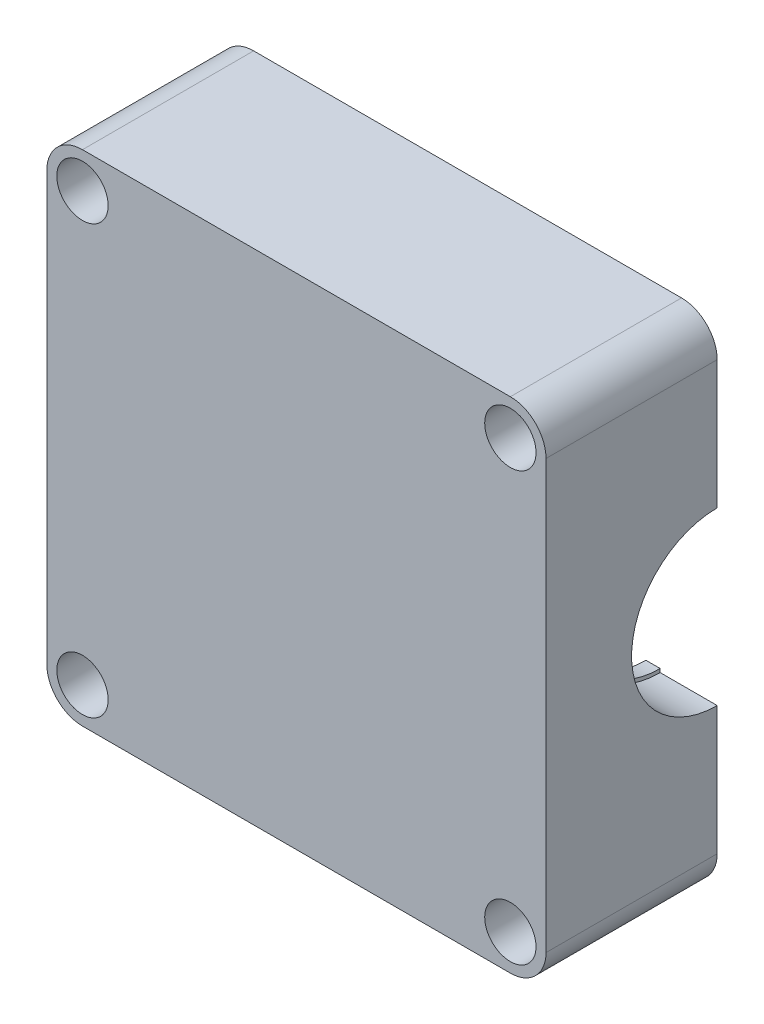
SolidWorks part; units mm, degrees
ref_plane "前视基准面" through (0, 0, 0) normal (0, 0, 1) x (1, 0, 0)
ref_plane "上视基准面" through (0, 0, 0) normal (0, 1, 0) x (1, 0, 0)
ref_plane "右视基准面" through (0, 0, 0) normal (1, 0, 0) x (0, 0, -1)
other "Configuration Table"
sketch "草图1" plane through (0, 0, 0) normal (0, 0, 1) x (-1, 0, 0)
  line L8 (-17.5, 15) -> (-17.5, -15)
  line L9 (-15, -17.5) -> (15, -17.5)
  line L10 (17.5, -15) -> (17.5, 15)
  line L11 (15, 17.5) -> (-15, 17.5)
  line L16 (15.6047, -11.417) -> (15.6047, 11.417)
  line L17 (-11.417, -15.6047) -> (11.417, -15.6047)
  line L18 (-15.6047, 11.417) -> (-15.6047, -11.417)
  line L19 (11.417, 15.6047) -> (-11.417, 15.6047)
  circle A2 centre (-15, -15) radius 1.8
  arc A8 (-15, 17.5) -> (-17.5, 15) centre (-15, 15) ccw
  arc A9 (-17.5, -15) -> (-15, -17.5) centre (-15, -15) ccw
  arc A10 (15, -17.5) -> (17.5, -15) centre (15, -15) ccw
  arc A11 (17.5, 15) -> (15, 17.5) centre (15, 15) ccw
  circle A12 centre (15, -15) radius 1.8
  circle A14 centre (15, 15) radius 1.8
  circle A16 centre (-15, 15) radius 1.8
  arc A38 (12.411, 14.7144) -> (14.7144, 12.411) centre (15, 15) ccw
  arc A39 (15.6047, 11.417) -> (14.7144, 12.411) centre (14.6048, 11.4171) ccw
  arc A40 (14.7144, -12.411) -> (15.6047, -11.417) centre (14.6048, -11.4171) ccw
  arc A41 (14.7144, -12.411) -> (12.411, -14.7144) centre (15, -15) ccw
  arc A42 (11.417, -15.6047) -> (12.411, -14.7144) centre (11.4171, -14.6048) ccw
  arc A43 (-12.411, -14.7144) -> (-11.417, -15.6047) centre (-11.4171, -14.6048) ccw
  arc A44 (-12.411, -14.7144) -> (-14.7144, -12.411) centre (-15, -15) ccw
  arc A45 (-15.6047, -11.417) -> (-14.7144, -12.411) centre (-14.6048, -11.4171) ccw
  arc A46 (-14.7144, 12.411) -> (-15.6047, 11.417) centre (-14.6048, 11.4171) ccw
  arc A47 (-14.7144, 12.411) -> (-12.411, 14.7144) centre (-15, 15) ccw
  arc A48 (-11.417, 15.6047) -> (-12.411, 14.7144) centre (-11.4171, 14.6048) ccw
  arc A49 (12.411, 14.7144) -> (11.417, 15.6047) centre (11.4171, 14.6048) ccw
extrude "凸台-拉伸1" add sketch "草图1" along normal blind 42
sketch "草图2" plane through (0, 17.5, 0) normal (0, 1, 0) x (1, 0, 0)
  line L0 (0, 0) -> (0, -12)
  circle A0 centre (0, -12) radius 6
  dimension "D2" = 12
  dimension "D1" = 12
extrude "切除-拉伸1" cut sketch "草图2" against normal through all
sketch "草图3" plane through (-17.5, 0, 0) normal (-1, 0, 0) x (0, 0, 1)
  line L0 (0, 0) -> (30, 0)
  circle A0 centre (30, 0) radius 6
  dimension "D2" = 12
  dimension "D1" = 30
extrude "切除-拉伸2" cut sketch "草图3" against normal through all
sketch "草图4" plane through (17.5, 0, 0) normal (1, 0, 0) x (0, 0, -1)
  line L0 (-30, 6) -> (-30, -18.5786)
  line L1 (-30, -18.5786) -> (7.9371, -18.5786)
  line L2 (7.9371, -18.5786) -> (5.1336, 19.1013)
  line L3 (5.1336, 19.1013) -> (-30, 19.1013)
  line L4 (-30, 19.1013) -> (-30, 6)
  circle A0 centre (-30, 0) radius 6 construction
extrude "切除-拉伸3" cut sketch "草图4" against normal through all contours L4 L0 L1 L2 L3
sketch "草图5" plane through (-15.6047, 0, 0) normal (1, 0, 0) x (0, 0, -1)
  line L0 (-30, -6.5) -> (-30, -6)
  line L1 (-30, 6) -> (-30, 6.5)
  arc A0 (-30, 6) -> (-30, -6) centre (-30, 0) ccw
  arc A1 (-30, 6.5) -> (-30, -6.5) centre (-30, 0) ccw
  dimension "D1" = 12
  dimension "D2" = 13
extrude "凸台-拉伸2" add sketch "草图5" along normal blind 2.1
sketch "草图6" plane through (-13.5047, 0, 0) normal (1, 0, 0) x (0, 0, -1)
  line L0 (-30, -6.5) -> (-30, -5.75)
  line L1 (-30, 5.75) -> (-30, 6.5)
  arc A0 (-30, 6.5) -> (-30, -6.5) centre (-30, 0) ccw
  arc A1 (-30, 5.75) -> (-30, -5.75) centre (-30, 0) ccw
  dimension "D1" = 13
  dimension "D2" = 11.5
extrude "凸台-拉伸3" add sketch "草图6" along normal blind 1
ref_plane "基准面1" through (0, 0, 0) normal (1, 0, 0) x (0, 0, -1)
mirror "镜向1" about plane through (0, 0, 0) normal (1, 0, 0) of "凸台-拉伸3", "凸台-拉伸2"
sketch "草图7" plane through (0, 0, 42) normal (0, 0, 1) x (1, 0, 0)
  line L0 (-15.6047, 11.417) -> (-15.6047, -11.417) construction
  line L1 (-11.417, -15.6047) -> (11.417, -15.6047) construction
  line L2 (15.6047, -11.417) -> (15.6047, 11.417) construction
  line L3 (11.417, 15.6047) -> (-11.417, 15.6047) construction
  line L12 (-15.6047, 11.417) -> (-15.6047, -11.417)
  line L13 (-11.417, -15.6047) -> (11.417, -15.6047)
  line L14 (15.6047, -11.417) -> (15.6047, 11.417)
  line L15 (11.417, 15.6047) -> (-11.417, 15.6047)
  line L16 (0, 0) -> (5, 0) construction
  line L17 (5, 0) -> (5, -5) construction
  line L18 (5, -5) -> (-5, -5) construction
  line L19 (-5, -5) -> (-5, 5) construction
  line L20 (-5, 5) -> (5, 5) construction
  line L21 (5, 5) -> (5, 0) construction
  arc A0 (-14.7144, 12.411) -> (-15.6047, 11.417) centre (-14.6048, 11.4171) ccw construction
  arc A1 (-15.6047, -11.417) -> (-14.7144, -12.411) centre (-14.6048, -11.4171) ccw construction
  arc A2 (-12.411, -14.7144) -> (-14.7144, -12.411) centre (-15, -15) ccw construction
  arc A3 (-12.411, -14.7144) -> (-11.417, -15.6047) centre (-11.4171, -14.6048) ccw construction
  arc A12 (11.417, -15.6047) -> (12.411, -14.7144) centre (11.4171, -14.6048) ccw construction
  arc A13 (14.7144, -12.411) -> (12.411, -14.7144) centre (15, -15) ccw construction
  arc A14 (14.7144, -12.411) -> (15.6047, -11.417) centre (14.6048, -11.4171) ccw construction
  arc A15 (15.6047, 11.417) -> (14.7144, 12.411) centre (14.6048, 11.4171) ccw construction
  arc A16 (12.411, 14.7144) -> (14.7144, 12.411) centre (15, 15) ccw construction
  arc A17 (12.411, 14.7144) -> (11.417, 15.6047) centre (11.4171, 14.6048) ccw construction
  arc A18 (-11.417, 15.6047) -> (-12.411, 14.7144) centre (-11.4171, 14.6048) ccw construction
  arc A19 (-14.7144, 12.411) -> (-12.411, 14.7144) centre (-15, 15) ccw construction
  arc A20 (-14.7144, 12.411) -> (-15.6047, 11.417) centre (-14.6048, 11.4171) ccw
  arc A21 (-15.6047, -11.417) -> (-14.7144, -12.411) centre (-14.6048, -11.4171) ccw
  arc A22 (-12.411, -14.7144) -> (-14.7144, -12.411) centre (-15, -15) ccw
  arc A23 (-12.411, -14.7144) -> (-11.417, -15.6047) centre (-11.4171, -14.6048) ccw
  arc A24 (11.417, -15.6047) -> (12.411, -14.7144) centre (11.4171, -14.6048) ccw
  arc A25 (14.7144, -12.411) -> (12.411, -14.7144) centre (15, -15) ccw
  arc A26 (14.7144, -12.411) -> (15.6047, -11.417) centre (14.6048, -11.4171) ccw
  arc A27 (15.6047, 11.417) -> (14.7144, 12.411) centre (14.6048, 11.4171) ccw
  arc A28 (12.411, 14.7144) -> (14.7144, 12.411) centre (15, 15) ccw
  arc A29 (12.411, 14.7144) -> (11.417, 15.6047) centre (11.4171, 14.6048) ccw
  arc A30 (-11.417, 15.6047) -> (-12.411, 14.7144) centre (-11.4171, 14.6048) ccw
  arc A31 (-14.7144, 12.411) -> (-12.411, 14.7144) centre (-15, 15) ccw
  dimension "D1" = 5
  dimension "D2" = 5
  dimension "D3" = 10
  dimension "D4" = 10
  dimension "D5" = 10
extrude "凸台-拉伸4" add sketch "草图7" against normal blind 2
